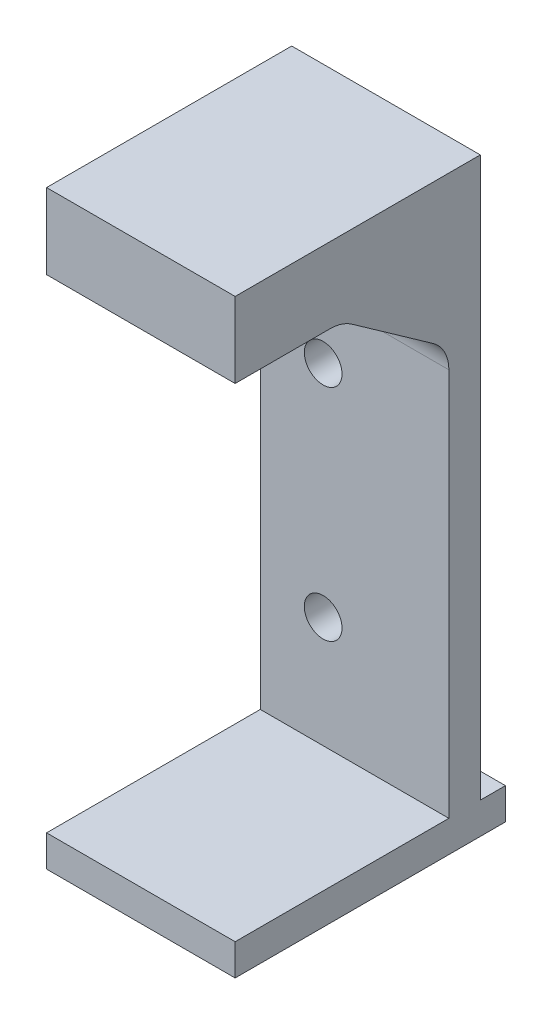
SolidWorks part; units mm, degrees
ref_plane "Front Plane" through (0, 0, 0) normal (0, 0, 1) x (1, 0, 0)
ref_plane "Top Plane" through (0, 0, 0) normal (0, 1, 0) x (1, 0, 0)
ref_plane "Right Plane" through (0, 0, 0) normal (1, 0, 0) x (0, 0, -1)
sketch "Sketch1" plane through (0, 0, 0) normal (0, 0, 1) x (1, 0, 0)
  line L0 (5, 26.35) -> (5, 8.85) construction
  line L1 (0, 0) -> (15, 0)
  line L2 (0, 0) -> (0, 28.85)
  line L3 (0, 28.85) -> (15, 28.85)
  line L4 (15, 0) -> (15, 28.85)
  circle A0 centre (5, 26.35) radius 1.5
  circle A1 centre (5, 8.85) radius 1.5
  dimension "D3" = 3
  dimension "D1" = 28.85
  dimension "D2" = 17.5
  dimension "D4" = 2.5
  dimension "D5" = 15
  dimension "D6" = 10
extrude "Boss-Extrude1" add sketch "Sketch1" along normal blind 2.5
sketch "Sketch3" plane through (0, 0, 2.5) normal (0, 0, 1) x (1, 0, 0)
  line L1 (0, 0) -> (15, 0)
  line L2 (0, 0) -> (0, -2)
  line L3 (0, -2) -> (15, -2)
  line L4 (15, 0) -> (15, -2)
  dimension "D1" = 2
  dimension "D2" = 15
extrude "Boss-Extrude2" add sketch "Sketch3" along normal blind 17 and the other way blind 4.5
sketch "Sketch4" plane through (0, 28.85, 0) normal (0, 1, 0) x (1, 0, 0)
  line L1 (0, 0) -> (15, 0)
  line L2 (0, 0) -> (0, -2.5)
  line L3 (0, -2.5) -> (15, -2.5)
  line L4 (15, 0) -> (15, -2.5)
extrude "Boss-Extrude3" add sketch "Sketch4" along normal blind 15.6
sketch "Sketch5" plane through (0, 0, 19.5) normal (0, 0, 1) x (1, 0, 0)
  line L1 (0, 0) -> (15, 0)
  line L2 (0, 0) -> (0, -2.5)
  line L3 (0, -2.5) -> (15, -2.5)
  line L4 (15, 0) -> (15, -2.5)
  dimension "D1" = 2.5
  dimension "D2" = 15
extrude "Boss-Extrude4" add sketch "Sketch5" against normal up to surface (21.5 mm away) up to face at (7.5, -1, -2)
sketch "Sketch6" plane through (0, 0, 2.5) normal (0, 0, 1) x (1, 0, 0)
  line L0 (15, 0) -> (15, 44.45) construction
  line L1 (0, 44.45) -> (15, 44.45)
  line L2 (0, 44.45) -> (0, 38.45)
  line L3 (0, 38.45) -> (15, 38.45)
  line L4 (15, 44.45) -> (15, 38.45)
  dimension "D1" = 6
extrude "Boss-Extrude5" add sketch "Sketch6" along normal up to surface (17 mm away)
sketch "Sketch7" plane through (15, 0, 0) normal (1, 0, 0) x (0, 0, -1)
  line L0 (-11, 38.45) -> (-2.5, 32.45)
  line L1 (-19.5, 38.45) -> (-2.5, 38.45) construction
  line L2 (-2.5, 0) -> (-2.5, 38.45) construction
  line L9 (-2.5, 0) -> (-19.5, 0)
  line L13 (-2.5, 38.45) -> (-2.5, 0)
  line L15 (-19.5, 0) -> (-19.5, -2.5)
  line L16 (2, -2.5) -> (2, 0)
  line L17 (2, 0) -> (0, 0)
  line L18 (-19.5, -2.5) -> (2, -2.5)
  line L19 (0, 0) -> (0, 44.45)
  line L20 (0, 44.45) -> (-19.5, 44.45)
  line L21 (-19.5, 44.45) -> (-19.5, 38.45)
  line L22 (-19.5, 38.45) -> (-2.5, 38.45)
  line L23 (-2.5, 38.45) -> (-2.5, 32.45)
  line L32 (-11, 38.45) -> (-2.5, 38.45)
  dimension "D1" = 6
  dimension "D2" = 0
extrude "Boss-Extrude10" add sketch "Sketch7" against normal up to surface (15 mm away) up to face at (0, 16.08, 7.9)
fillet "Fillet1" radius 3 2 edges at (7.5, 32.45, 2.5) (7.5, 38.45, 11)
